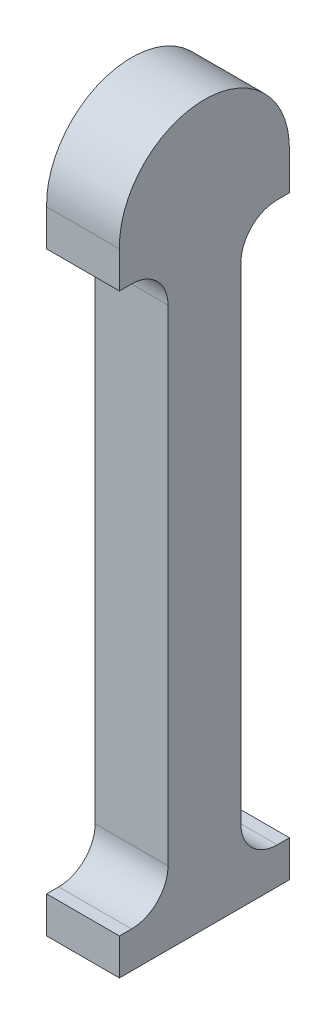
SolidWorks part; units mm, degrees
ref_plane "Front Plane" through (0, 0, 0) normal (0, 0, 1) x (1, 0, 0)
ref_plane "Top Plane" through (0, 0, 0) normal (0, 1, 0) x (1, 0, 0)
ref_plane "Right Plane" through (0, 0, 0) normal (1, 0, 0) x (0, 0, -1)
sketch "Sketch1" plane through (0, 0, 0) normal (0, 1, 0) x (1, 0, 0)
  line L1 (-1.5, -1.5) -> (1.5, -1.5)
  line L2 (-1.5, -1.5) -> (-1.5, 1.5)
  line L3 (-1.5, 1.5) -> (1.5, 1.5)
  line L4 (1.5, -1.5) -> (1.5, 1.5)
  line L5 (-1.5, -1.5) -> (1.5, 1.5) construction
  line L6 (-1.5, 1.5) -> (1.5, -1.5) construction
  point P0 (0, 0)
  dimension "D1" = 3
  dimension "D2" = 3
extrude "Boss-Extrude1" add sketch "Sketch1" along normal blind 23
sketch "Sketch3" plane through (0, 23, 0) normal (0, 1, 0) x (1, 0, 0)
  line L1 (-1.5, 3.5) -> (1.5, 3.5)
  line L2 (-1.5, 3.5) -> (-1.5, -3.5)
  line L3 (-1.5, -3.5) -> (1.5, -3.5)
  line L4 (1.5, 3.5) -> (1.5, -3.5)
  line L5 (-1.5, 3.5) -> (1.5, -3.5) construction
  line L6 (-1.5, -3.5) -> (1.5, 3.5) construction
  point P0 (0, 0)
  dimension "D1" = 3
  dimension "D2" = 7
extrude "Boss-Extrude2" add sketch "Sketch3" along normal blind 1.5
ref_plane "Plane1" through (0, 11.5, 0) normal (0, -1, 0) x (-1, 0, 0)
mirror "Mirror2" about plane through (0, 11.5, 0) normal (0, -1, 0) of "Boss-Extrude2"
fillet "Fillet1" radius 1.5 4 edges at (0, 0, 1.5) (0, 0, -1.5) (0, 23, -1.5) (0, 23, 1.5)
sketch "Sketch4" plane through (-1.5, 0, 0) normal (-1, 0, 0) x (0, 0, 1)
  line L0 (0, -2.9622) -> (0, 30.0135) construction
  line L1 (-3.5, 24.5) -> (3.5, 24.5)
  arc A0 (3.5, 24.5) -> (-3.5, 24.5) centre (0, 24.5767) ccw
  point P9 (-3.5, 24.5)
  dimension "D1" = 7.0017
extrude "Boss-Extrude3" add sketch "Sketch4" against normal blind 3
